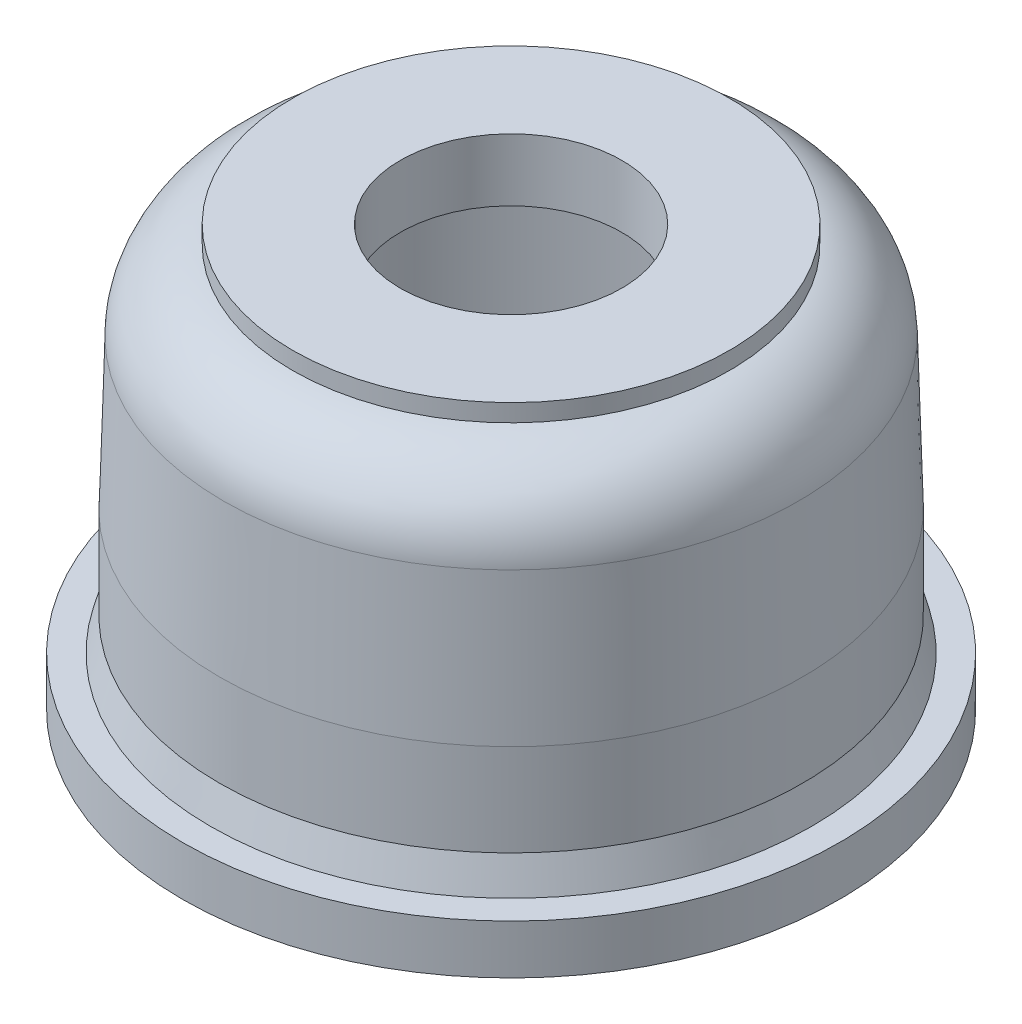
SolidWorks part; units mm, degrees
material "EPİKLORHİDRİN"
ref_plane "Ön Düzlem" through (0, 0, 0) normal (0, 0, 1) x (1, 0, 0)
ref_plane "Üst Düzlem" through (0, 0, 0) normal (0, 1, 0) x (1, 0, 0)
ref_plane "Sağ Düzlem" through (0, 0, 0) normal (1, 0, 0) x (0, 0, -1)
sketch "Çizim1" plane through (0, 0, 0) normal (0, 0, 1) x (1, 0, 0)
  line L0 (0, 0) -> (0, -3.7937)
  line L1 (6.6379, -1.0081) -> (6.6379, 0)
  line L2 (6.6379, 0) -> (0, 0)
  line L3 (7.2927, -2.3951) -> (7.2927, -1.3961)
  line L4 (6.738, -3.7937) -> (6.738, -2.7238)
  line L5 (6.738, -2.7238) -> (7.2927, -2.3951)
  line L6 (6.6379, -1.0081) -> (7.2927, -1.3961)
  line L7 (6.6379, 0) -> (13.2867, 0)
  line L8 (13.2867, 0) -> (13.2867, -1.0643)
  line L9 (12.6873, -0.3696) -> (12.6873, -1.968)
  line L10 (9.99, -0.3696) -> (12.6873, -0.3696)
  line L11 (12.6873, -1.968) -> (10.7892, -1.968)
  line L12 (7.992, -2.3676) -> (7.992, -3.4665)
  line L13 (9.2907, -3.4665) -> (7.992, -3.4665)
  line L14 (0, -3.7937) -> (10.989, -3.7937)
  line L15 (15.984, -8.7887) -> (15.984, -20.2531)
  line L16 (17.7322, -20.5794) -> (17.7322, -14.9825)
  line L17 (18.2817, -22.5774) -> (17.7322, -20.5794)
  line L18 (19.98, -22.5774) -> (18.2817, -22.5774)
  line L19 (19.98, -22.5774) -> (19.98, -25.5744)
  line L20 (19.98, -25.5744) -> (17.1447, -25.5744)
  line L21 (18.7276, -25.4097) -> (16.2338, -24.2468)
  line L22 (19.5804, -22.9271) -> (19.5804, -25.0749)
  line L23 (19.0809, -22.9271) -> (19.0809, -24.7096)
  line L24 (19.0809, -22.9271) -> (19.5804, -22.9271)
  line L25 (18.7967, -24.8907) -> (16.2338, -23.6956)
  line L26 (16.2338, -21.0814) -> (16.2338, -23.6956)
  line L27 (17.7322, -14.9825) -> (17.475, -5.8533)
  line L28 (16.2338, -24.5779) -> (16.2338, -24.2468)
  line L29 (17.1447, -25.5744) -> (17.1079, -25.5691)
  arc A0 (10.7892, -1.968) -> (9.2907, -3.4665) centre (10.7892, -3.4665) ccw
  arc A1 (9.99, -0.3696) -> (7.992, -2.3676) centre (9.99, -2.3676) ccw
  arc A2 (15.984, -8.7887) -> (10.989, -3.7937) centre (10.989, -8.7887) ccw
  arc A3 (17.475, -5.8533) -> (13.2867, -1.0643) centre (12.4819, -5.994) ccw
  arc A4 (16.2338, -21.0814) -> (15.984, -20.2531) centre (14.7353, -21.0814) ccw
  arc A5 (16.2338, -24.5779) -> (17.1079, -25.5691) centre (17.2328, -24.5779) ccw
  arc A6 (18.7276, -25.4097) -> (19.5804, -25.0749) centre (19.0611, -25.0056) ccw
  arc A7 (18.7967, -24.8907) -> (19.0809, -24.7096) centre (18.8811, -24.7096) ccw
revolve "Döndür5" add sketch "Çizim1" angle 360 about L0
sketch "Çizim2" plane through (0, 0, 0) normal (0, 1, 0) x (1, 0, 0)
  circle A0 centre (0, 0) radius 6.74
extrude "Kes-Ekstrüzyon2" cut sketch "Çizim2" against normal blind 10
